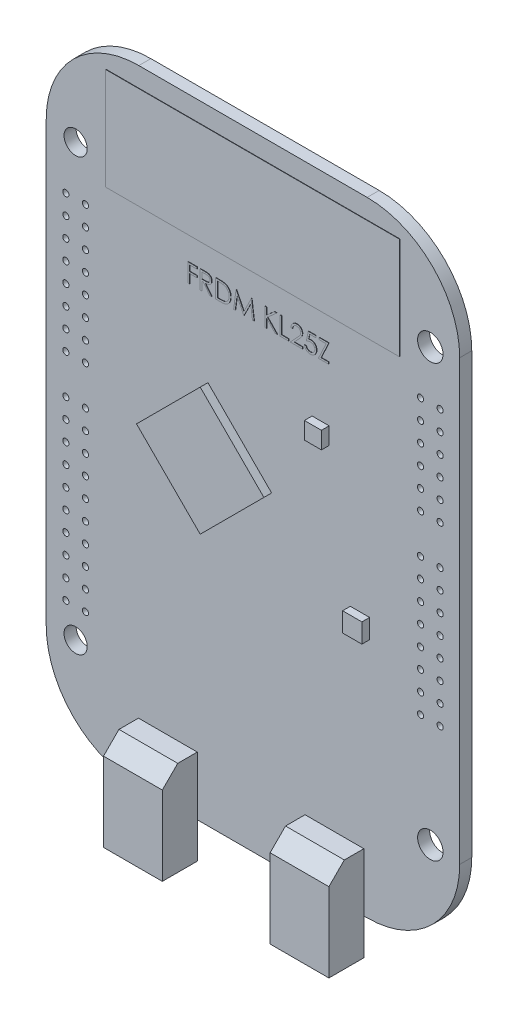
SolidWorks part; units mm, degrees
ref_plane "Přední rovina" through (0, 0, 0) normal (0, 0, 1) x (1, 0, 0)
ref_plane "Horní rovina" through (0, 0, 0) normal (0, 1, 0) x (1, 0, 0)
ref_plane "Pravá rovina" through (0, 0, 0) normal (1, 0, 0) x (0, 0, -1)
sketch "Skica1" plane through (0, 0, 0) normal (0, 0, 1) x (1, 0, 0)
  line L1 (-14.795, -40.435) -> (14.795, -40.435)
  line L2 (-26.795, -28.435) -> (-26.795, 28.435)
  line L3 (-14.795, 40.435) -> (14.795, 40.435)
  line L4 (26.795, -28.435) -> (26.795, 28.435)
  line L5 (-26.795, -40.435) -> (26.795, 40.435) construction
  line L6 (-26.795, 40.435) -> (26.795, -40.435) construction
  arc A0 (-14.795, -40.435) -> (-26.795, -28.435) centre (-14.795, -28.435) cw
  arc A1 (14.795, -40.435) -> (26.795, -28.435) centre (14.795, -28.435) ccw
  arc A2 (14.795, 40.435) -> (26.795, 28.435) centre (14.795, 28.435) cw
  arc A3 (-26.795, 28.435) -> (-14.795, 40.435) centre (-14.795, 28.435) cw
  point P0 (0, 0)
  point P1 (0, 0)
  point P8 (0, 0)
  dimension "D1" = 80.87
  dimension "D3" = 12
  dimension "D2" = 53.59
extrude "Přidat vysunutím1" add sketch "Skica1" along normal blind 1.56
sketch "Skica2" plane through (0, 0, 1.56) normal (0, 0, 1) x (1, 0, 0)
  line L0 (14.795, 40.435) -> (-14.795, 40.435) construction
  line L1 (-26.795, 28.435) -> (-26.795, -28.435) construction
  circle A0 centre (-21.715, 21.385) radius 0.4
  circle A1 centre (-24.255, 21.385) radius 0.4
  dimension "D3" = 0.8
  dimension "D4" = 2.54
  dimension "D1" = 19.05
  dimension "D2" = 5.08
extrude "Odebrat vysunutím1" cut sketch "Skica2" against normal blind 1.56
pattern_linear "LinPole1" count 8 spacing 2.54 along (0, -1, 0) of "Odebrat vysunutím1"
sketch "Skica3" plane through (0, 0, 1.56) normal (0, 0, 1) x (1, 0, 0)
  line L0 (-24.255, 3.605) -> (-24.255, -2.766) construction
  line L1 (-24.255, -1.475) -> (-21.715, -1.475) construction
  circle A0 centre (-24.255, -1.475) radius 0.4
  circle A1 centre (-21.715, -1.475) radius 0.4
  circle A2 centre (-24.255, 3.605) radius 0.4 construction
  dimension "D1" = 2.54
  dimension "D2" = 5.08
extrude "Odebrat vysunutím2" cut sketch "Skica3" against normal blind 1.56
pattern_linear "LinPole2" count 10 spacing 2.54 along (0, -1, 0) of "Odebrat vysunutím2"
sketch "Skica4" plane through (0, 0, 0) normal (0, 0, -1) x (-1, 0, 0)
  line L0 (-14.795, 40.435) -> (14.795, 40.435) construction
  line L2 (-26.795, -28.435) -> (-26.795, 28.435) construction
  circle A0 centre (-24.255, 21.385) radius 0.4
  circle A1 centre (-21.715, 21.385) radius 0.4
  circle A2 centre (21.715, 21.385) radius 0.4 construction
  dimension "D1" = 2.54
  dimension "D2" = 19.05
  dimension "D3" = 5.08
extrude "Odebrat vysunutím3" cut sketch "Skica4" against normal blind 1.56
pattern_linear "LinPole3" count 6 spacing 2.54 along (0, -1, 0) of "Odebrat vysunutím3"
sketch "Skica5" plane through (0, 0, 0) normal (0, 0, -1) x (-1, 0, 0)
  line L0 (-24.255, 3.605) -> (-21.715, 3.605) construction
  line L1 (-24.255, 8.685) -> (-24.255, 3.605) construction
  circle A0 centre (-24.255, 3.605) radius 0.4
  circle A1 centre (-21.715, 3.605) radius 0.4
  circle A2 centre (-24.255, 8.685) radius 0.4 construction
  dimension "D1" = 5.08
  dimension "D2" = 2.54
extrude "Odebrat vysunutím4" cut sketch "Skica5" against normal blind 1.56
pattern_linear "LinPole4" count 8 spacing 2.54 along (0, -1, 0) of "Odebrat vysunutím4"
sketch "Skica6" plane through (0, 0, 1.56) normal (0, 0, 1) x (1, 0, 0)
  line L0 (0, 40.435) -> (0, -40.435) construction
  line L1 (-19.05, 24.6881) -> (19.05, 24.6881)
  line L2 (-19.05, 24.6881) -> (-19.05, 37.895)
  line L3 (-19.05, 37.895) -> (19.05, 37.895)
  line L4 (19.05, 24.6881) -> (19.05, 37.895)
  line L5 (-19.05, 24.6881) -> (19.05, 37.895) construction
  line L6 (-19.05, 37.895) -> (19.05, 24.6881) construction
  line L7 (14.795, 40.435) -> (-14.795, 40.435) construction
  line L8 (-14.795, -40.435) -> (14.795, -40.435) construction
  text T0 "FRDM KL25Z" font "Century Gothic" height in points 9
  point P1 (0, 31.2916)
  dimension "D1" = 38.1
  dimension "D2" = 2.54
extrude "Přidat vysunutím2" add sketch "Skica6" along normal blind 0.05
sketch "Skica7" plane through (0, 0, 1.56) normal (0, 0, 1) x (1, 0, 0)
  line L0 (14.795, 40.435) -> (-14.795, 40.435) construction
  line L1 (-26.795, 28.435) -> (-26.795, -28.435) construction
  line L2 (-22.985, 27.735) -> (22.985, 27.735) construction
  line L3 (26.795, -28.435) -> (26.795, 28.435) construction
  circle A0 centre (-22.985, 27.735) radius 1.5026
  circle A1 centre (22.985, 27.735) radius 1.6482
  dimension "D1" = 12.7
  dimension "D2" = 3.81
  dimension "D3" = 3.81
extrude "Odebrat vysunutím5" cut sketch "Skica7" against normal up to vertex (1.56 mm away)
pattern_linear "LinPole5" count 2 spacing 55.88 along (0, -1, 0) of "Odebrat vysunutím5"
sketch "Skica8" plane through (0, 0, 1.56) normal (0, 0, 1) x (1, 0, 0)
  line L0 (-14.095, 1.065) -> (-5.84, 9.32)
  line L1 (-5.84, 9.32) -> (2.415, 1.065)
  line L2 (2.415, 1.065) -> (-5.84, -7.19)
  line L3 (-5.84, -7.19) -> (-14.095, 1.065)
  line L4 (-26.795, 28.435) -> (-26.795, -28.435) construction
  line L5 (-24.255, 3.205) -> (-24.255, -1.075) construction
  line L6 (-24.255, 1.065) -> (-14.095, 1.065) construction
  circle A0 centre (-24.255, 3.605) radius 0.4 construction
  circle A1 centre (-24.255, -1.475) radius 0.4 construction
  dimension "D1" = 12.7
  dimension "D2" = 16.51
extrude "Přidat vysunutím3" add sketch "Skica8" along normal blind 1
sketch "Skica9" plane through (0, 0, 1.56) normal (0, 0, 1) x (1, 0, 0)
  line L1 (7.4962, 12.495) -> (10.035, 12.495)
  line L2 (7.4962, 12.495) -> (7.4962, 9.9562)
  line L3 (7.4962, 9.9562) -> (10.035, 9.9562)
  line L4 (10.035, 12.495) -> (10.035, 9.9562)
  line L5 (7.4962, 12.495) -> (10.035, 9.9562) construction
  line L6 (7.4962, 9.9562) -> (10.035, 12.495) construction
  line L7 (14.795, 40.435) -> (-14.795, 40.435) construction
  line L8 (-26.795, 28.435) -> (-26.795, -28.435) construction
  line L10 (7.6635, 10.1235) -> (9.8678, 10.1235)
  line L11 (7.6635, 10.1235) -> (7.6635, 12.3278)
  line L12 (7.6635, 12.3278) -> (9.8678, 12.3278)
  line L13 (9.8678, 10.1235) -> (9.8678, 12.3278)
  line L14 (7.6635, 10.1235) -> (9.8678, 12.3278) construction
  line L15 (7.6635, 12.3278) -> (9.8678, 10.1235) construction
  point P0 (8.7656, 11.2256)
  point P9 (8.7656, 11.2256)
  dimension "D1" = 36.83
  dimension "D2" = 27.94
extrude "Přidat vysunutím6" add sketch "Skica9" along normal blind 1 contours L12 L13 L10 L11
sketch "Skica13" plane through (0, 0, 1.56) normal (0, 0, 1) x (1, 0, 0)
  line L0 (-26.795, 28.435) -> (-26.795, -28.435) construction
  line L1 (12.615, -6.555) -> (15.115, -6.555)
  line L2 (12.615, -6.555) -> (12.615, -9.055)
  line L3 (12.615, -9.055) -> (15.115, -9.055)
  line L4 (15.115, -6.555) -> (15.115, -9.055)
  line L5 (12.615, -6.555) -> (15.115, -9.055) construction
  line L6 (12.615, -9.055) -> (15.115, -6.555) construction
  line L7 (14.795, 40.435) -> (-14.795, 40.435) construction
  point P0 (13.865, -7.805)
  dimension "D1" = 41.91
  dimension "D2" = 46.99
  dimension "D3" = 2.5
extrude "Přidat vysunutím8" add sketch "Skica13" along normal blind 1
sketch "Skica14" plane through (0, 0, 1.56) normal (0, 0, 1) x (1, 0, 0)
  line L0 (-14.795, -40.435) -> (14.795, -40.435) construction
  line L1 (-14.841, -45.085) -> (-7.221, -45.085)
  line L2 (-14.841, -45.085) -> (-14.841, -32.835)
  line L3 (-14.841, -32.835) -> (-7.221, -32.835)
  line L4 (-7.221, -45.085) -> (-7.221, -32.835)
  line L5 (-14.841, -45.085) -> (-7.221, -32.835) construction
  line L6 (-14.841, -32.835) -> (-7.221, -45.085) construction
  line L7 (6.749, -45.1354) -> (14.369, -45.1354)
  line L8 (6.749, -45.1354) -> (6.749, -32.8854)
  line L9 (6.749, -32.8854) -> (14.369, -32.8854)
  line L10 (14.369, -45.1354) -> (14.369, -32.8854)
  line L11 (6.749, -45.1354) -> (14.369, -32.8854) construction
  line L12 (6.749, -32.8854) -> (14.369, -45.1354) construction
  point P0 (-11.031, -38.96)
  point P5 (10.559, -39.0104)
  dimension "D1" = 7.62
  dimension "D2" = 13.97
  dimension "D3" = 7.6
  dimension "D4" = 12.25
extrude "Přidat vysunutím9" add sketch "Skica14" along normal blind 4.53
sketch "Skica16" plane through (0, -45.085, 0) normal (0, -1, 0) x (1, 0, 0)
  line L0 (-14.841, 6.09) -> (-14.841, 1.56) construction
  line L1 (-7.221, 6.09) -> (-7.221, 1.56) construction
  line L2 (-14.841, 1.56) -> (-7.221, 1.56) construction
  line L4 (6.749, 6.09) -> (6.749, 1.56) construction
  line L5 (-14.841, 6.09) -> (-7.221, 6.09) construction
  line L6 (-14.431, 1.97) -> (-7.631, 1.97)
  line L7 (-14.431, 1.97) -> (-14.431, 5.68)
  line L8 (-14.431, 5.68) -> (-7.631, 5.68)
  line L9 (-7.631, 1.97) -> (-7.631, 5.68)
  line L10 (6.749, 6.09) -> (14.369, 6.09) construction
  line L11 (14.369, 6.09) -> (14.369, 1.56) construction
  line L12 (6.749, 1.56) -> (14.369, 1.56) construction
  line L19 (13.959, 1.97) -> (7.159, 1.97)
  line L20 (13.959, 1.97) -> (13.959, 5.68)
  line L21 (13.959, 5.68) -> (7.159, 5.68)
  line L22 (7.159, 1.97) -> (7.159, 5.68)
  point P3 (-11.031, 3.825)
  point P9 (10.559, 3.825)
  point P28 (10.559, 3.825)
  dimension "D1" = 0.41
  dimension "D2" = 0.41
  dimension "D3" = 0.41
  dimension "D4" = 0.41
  dimension "D5" = 0.41
  dimension "D6" = 0.41
  dimension "D7" = 0.41
  dimension "D8" = 0.41
extrude "Odebrat vysunutím10" cut sketch "Skica16" against normal blind 6 contours L22 L19 L20 L21 | L8 L9 L6 L7
sketch "Skica17" plane through (0, -45.1354, 0) normal (0, -1, 0) x (-1, 0, 0)
  line L8 (7.631, -1.97) -> (7.631, -5.68) construction
  line L9 (-13.959, -1.97) -> (-7.159, -1.97)
  line L10 (-13.959, -1.97) -> (-13.959, -5.68)
  line L11 (-13.959, -5.68) -> (-7.159, -5.68)
  line L12 (-7.159, -1.97) -> (-7.159, -5.68)
  point P0 (-10.559, -3.825)
  point P10 (-9.4888, -4.5383)
extrude "Odebrat vysunutím11" cut sketch "Skica17" against normal blind 6
sketch "Skica18" plane through (0, 0, 1.97) normal (0, 0, 1) x (1, 0, 0)
  line L1 (-14.431, -39.085) -> (-7.631, -39.085)
  line L2 (-14.431, -39.085) -> (-14.431, -45.085)
  line L3 (-14.431, -45.085) -> (-7.631, -45.085)
  line L4 (-7.631, -39.085) -> (-7.631, -45.085)
  line L5 (7.159, -39.085) -> (13.959, -39.085)
  line L6 (7.159, -39.085) -> (7.159, -45.1354)
  line L7 (7.159, -45.1354) -> (13.959, -45.1354)
  line L8 (13.959, -39.085) -> (13.959, -45.1354)
extrude "Přidat vysunutím10" add sketch "Skica18" along normal blind 1.2
chamfer "Zkosení1" distance 2 angle 45 2 edges at (10.559, -32.8854, 6.09) (-11.031, -32.835, 6.09)
